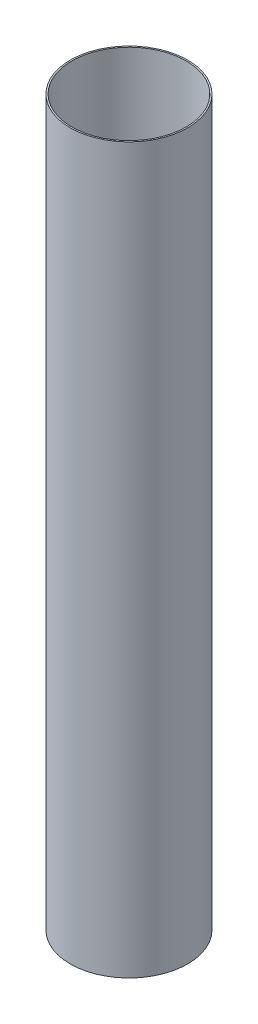
SolidWorks part; units mm, degrees
material "AISI 304"
ref_plane "Piano frontale" through (0, 0, 0) normal (0, 0, 1) x (1, 0, 0)
ref_plane "Piano superiore" through (0, 0, 0) normal (0, 1, 0) x (1, 0, 0)
ref_plane "Piano destro" through (0, 0, 0) normal (1, 0, 0) x (0, 0, -1)
sketch "Schizzo1" plane through (0, 0, 0) normal (0, 1, 0) x (1, 0, 0)
  circle A0 centre (0, 0) radius 60
extrude "Estrusione-Sottile1" add sketch "Schizzo1" along normal mid plane 740 thin thin type one direction reverse wall 1.5
